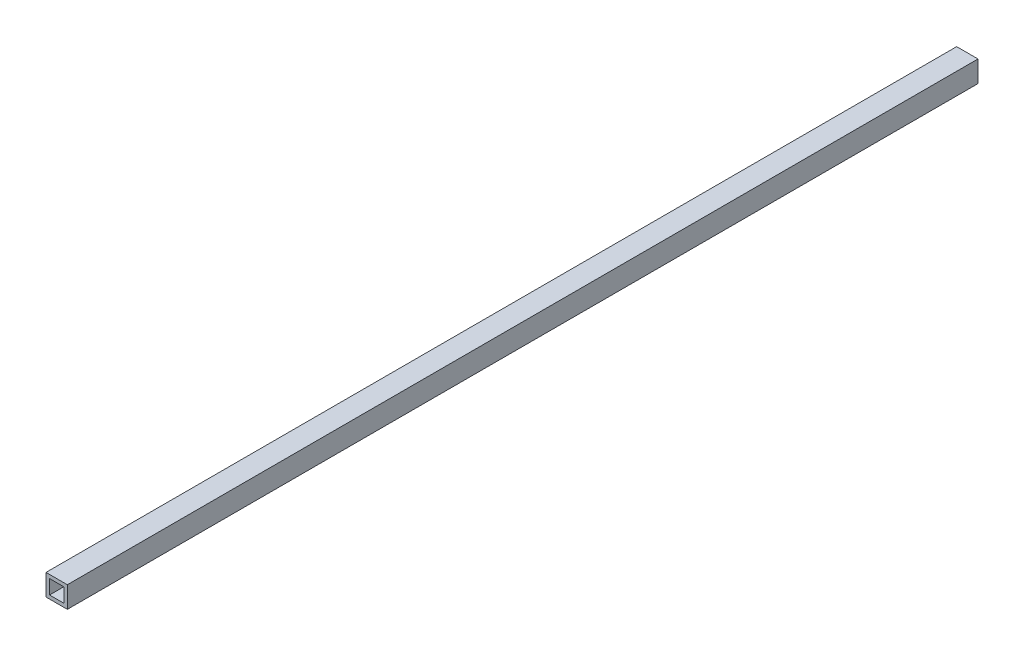
SolidWorks part; units mm, degrees
ref_plane "Front Plane" through (0, 0, 0) normal (0, 0, 1) x (1, 0, 0)
ref_plane "Top Plane" through (0, 0, 0) normal (0, 1, 0) x (1, 0, 0)
ref_plane "Right Plane" through (0, 0, 0) normal (1, 0, 0) x (0, 0, -1)
sketch "Sketch1" plane through (0, 0, 0) normal (0, 0, 1) x (1, 0, 0)
  line L1 (392.169, 203.2) -> (411.219, 203.2)
  line L2 (392.169, 203.2) -> (392.169, 184.15)
  line L3 (392.169, 184.15) -> (411.219, 184.15)
  line L4 (411.219, 203.2) -> (411.219, 184.15)
  dimension "D1" = 19.05
  dimension "D2" = 19.05
extrude "Boss-Extrude1" add sketch "Sketch1" along normal blind 812.8
sketch "Sketch2" plane through (0, 0, 0) normal (0, 0, -1) x (-1, 0, 0)
  line L8 (-395.344, 187.325) -> (-395.344, 200.025)
  line L9 (-395.344, 200.025) -> (-408.044, 200.025)
  line L10 (-408.044, 200.025) -> (-408.044, 187.325)
  line L11 (-408.044, 187.325) -> (-395.344, 187.325)
  line L12 (-395.344, 187.325) -> (-395.344, 200.025)
  line L13 (-395.344, 200.025) -> (-408.044, 200.025)
  line L14 (-408.044, 200.025) -> (-408.044, 187.325)
  line L15 (-408.044, 187.325) -> (-395.344, 187.325)
  dimension "D1" = 3.175
extrude "Cut-Extrude1" cut sketch "Sketch2" against normal blind 812.8
